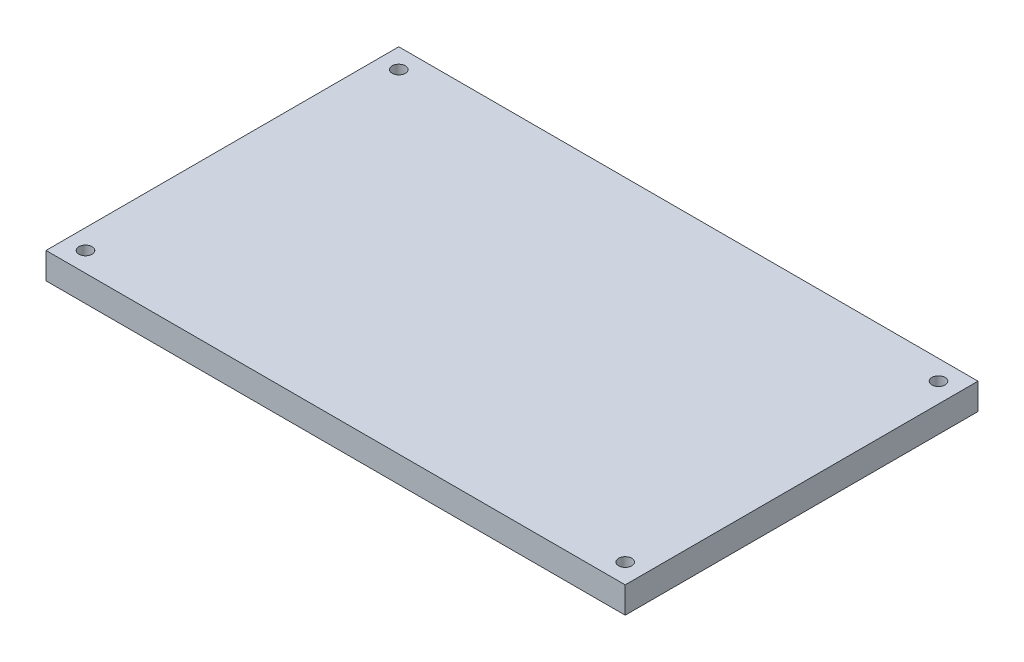
SolidWorks part; units mm, degrees
material "ABS"
ref_plane "Front Plane" through (0, 0, 0) normal (0, 0, 1) x (1, 0, 0)
ref_plane "Top Plane" through (0, 0, 0) normal (0, 1, 0) x (1, 0, 0)
ref_plane "Right Plane" through (0, 0, 0) normal (1, 0, 0) x (0, 0, -1)
sketch "Sketch2" plane through (0, 0, 0) normal (0, 1, 0) x (1, 0, 0)
  line L0 (0, 85.09) -> (139.7, 85.09)
  line L1 (0, 85.09) -> (0, 0)
  line L2 (0, 0) -> (139.7, 0)
  line L3 (139.7, 85.09) -> (139.7, 0)
  circle A0 centre (4.7625, 80.3275) radius 1.5875
  circle A1 centre (4.7625, 4.7625) radius 1.5875
  circle A2 centre (134.9375, 4.7625) radius 1.5875
  circle A3 centre (134.9375, 80.3275) radius 1.5875
  dimension "D3" = 3.175
  dimension "D6" = 4.7625
  dimension "D1" = 139.7
  dimension "D2" = 85.09
  dimension "D4" = 130.175
  dimension "D5" = 75.565
  dimension "D7" = 4.7625
extrude "Boss-Extrude1" add sketch "Sketch2" along normal blind 6.35
